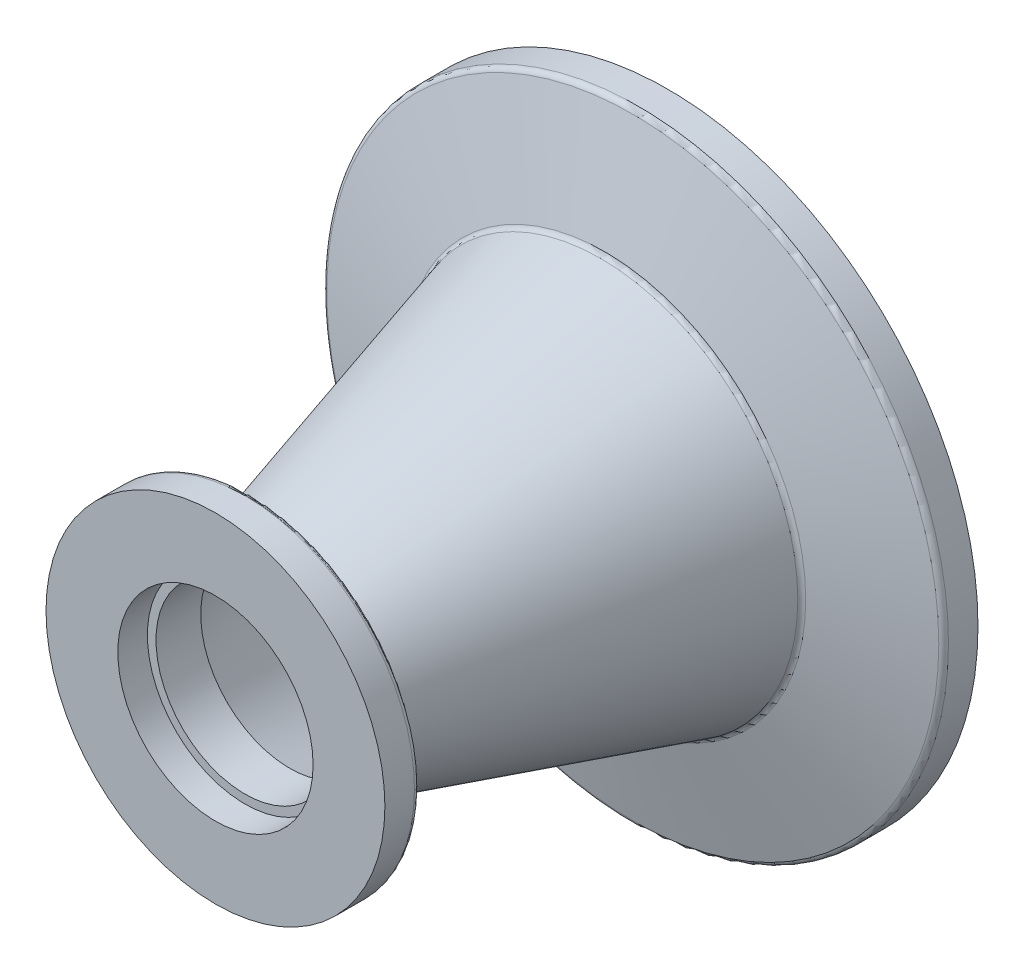
SolidWorks part; units mm, degrees
ref_plane "Front Plane" through (0, 0, 0) normal (0, 0, 1) x (1, 0, 0)
ref_plane "Top Plane" through (0, 0, 0) normal (0, 1, 0) x (1, 0, 0)
ref_plane "Right Plane" through (0, 0, 0) normal (1, 0, 0) x (0, 0, -1)
sketch "Sketch1" plane through (0, 0, 0) normal (1, 0, 0) x (0, 0, -1)
  line L0 (20.0025, -27.432) -> (20.0025, 27.432) construction
  line L1 (-20.0025, -14.986) -> (-20.0025, 14.986) construction
  line L2 (-20.0025, 0) -> (20.0025, 0) construction
  line L3 (-17.3863, 7.874) -> (-13.431, 7.874)
  line L4 (-13.431, 7.874) -> (17.3863, 16.6537)
  line L5 (-20.0025, 8.636) -> (-17.3863, 8.636)
  line L6 (-17.3863, 8.636) -> (-17.3863, 7.874)
  line L7 (20.0025, 20.6502) -> (17.3863, 20.6502)
  line L8 (-20.0025, 14.986) -> (-17.0053, 14.986)
  line L9 (20.0025, 27.432) -> (17.0053, 27.432)
  line L10 (-17.0053, 14.986) -> (-15.4087, 9.0273)
  line L11 (17.0053, 27.432) -> (14.3451, 17.5039)
  line L12 (-15.4087, 9.0273) -> (14.3451, 17.5039)
  line L13 (20.0025, 20.6502) -> (20.0025, 27.432)
  line L14 (-20.0025, 8.636) -> (-20.0025, 14.986)
  line L16 (17.3863, 20.6502) -> (17.3863, 16.6537)
  line L18 (-15.4087, 7.874) -> (-15.4087, 9.0273) construction
  point P6 (20.0025, 19.05)
  point P7 (20.0025, -19.05)
  point P9 (-20.0025, 9.525)
  point P10 (-20.0025, -9.525)
  point P11 (-20.0025, -8.636)
  point P12 (20.0025, -20.6502)
  point P13 (-20.0025, 8.636)
  point P14 (20.0025, 20.6502)
  point P29 (20.0025, 17.399)
  dimension "Flange OD 2" = 29.972
  dimension "Flange OD 1" = 54.864
  dimension "For Tube OD 1" = 38.1
  dimension "For Tube OD 2" = 19.05
  dimension "Length" = 40.005
  dimension "Connection ID 1" = 41.3004
  dimension "Connection ID 2" = 17.272
  dimension "Connection Depth" = 2.6162
  dimension "ID 2" = 15.748
  dimension "Flange Flat Thickness" = 2.9972
  dimension "D1" = 105
  dimension "D2" = 105
  dimension "Wall Thickness" = 1.651
  dimension "ID 1" = 34.798
sketch "Sketch2" plane through (0, 0, 0) normal (1, 0, 0) x (0, 0, -1)
  line L0 (20.0025, 27.432) -> (17.0053, 27.432) construction
  line L1 (17.0053, 27.432) -> (14.3451, 17.5039) construction
  line L2 (20.0025, 20.6502) -> (20.0025, 27.432) construction
  line L3 (20.0025, 20.6502) -> (17.3863, 20.6502) construction
  line L5 (-17.3863, 8.636) -> (-17.3863, 7.874) construction
  line L6 (-17.3863, 7.874) -> (-13.431, 7.874) construction
  line L7 (-20.0025, 8.636) -> (-17.3863, 8.636) construction
  line L8 (-15.4087, 9.0273) -> (14.3451, 17.5039) construction
  line L9 (-17.0053, 14.986) -> (-15.4087, 9.0273) construction
  line L10 (-20.0025, 14.986) -> (-17.0053, 14.986) construction
  line L11 (-20.0025, 8.636) -> (-20.0025, 14.986) construction
  line L12 (20.0025, 27.432) -> (17.389, 27.432)
  line L13 (16.906, 27.0614) -> (14.4184, 17.7777)
  line L14 (20.0025, 20.6502) -> (20.0025, 27.432)
  line L15 (20.0025, 20.6502) -> (17.3863, 20.6502)
  line L17 (-17.3863, 8.636) -> (-17.3863, 7.874)
  line L18 (-17.3863, 7.874) -> (-13.431, 7.874)
  line L19 (-20.0025, 8.636) -> (-17.3863, 8.636)
  line L20 (-14.9202, 9.1664) -> (14.0725, 17.4263)
  line L21 (-16.906, 14.6154) -> (-15.5401, 9.5179)
  line L22 (-20.0025, 14.986) -> (-17.389, 14.986)
  line L23 (-20.0025, 8.636) -> (-20.0025, 14.986)
  line L24 (-13.431, 7.874) -> (17.3863, 16.6537)
  line L25 (17.3863, 16.6537) -> (17.3863, 20.6502)
  arc A0 (17.389, 27.432) -> (16.906, 27.0614) centre (17.389, 26.932) ccw
  arc A1 (14.4184, 17.7777) -> (14.0725, 17.4263) centre (13.9355, 17.9071) cw
  arc A2 (-17.389, 14.986) -> (-16.906, 14.6154) centre (-17.389, 14.486) cw
  arc A3 (-15.5401, 9.5179) -> (-14.9202, 9.1664) centre (-15.0572, 9.6473) ccw
  dimension "D1" = 0.5
revolve "Revolve1" add sketch "Sketch2" angle 360 about L2
equation "\"ID 2@Sketch1\"=\"For Tube OD 2@Sketch1\"-.13"
equation "\"ID 1@Sketch1\" = \"For Tube OD 1@Sketch1\" - .13"
